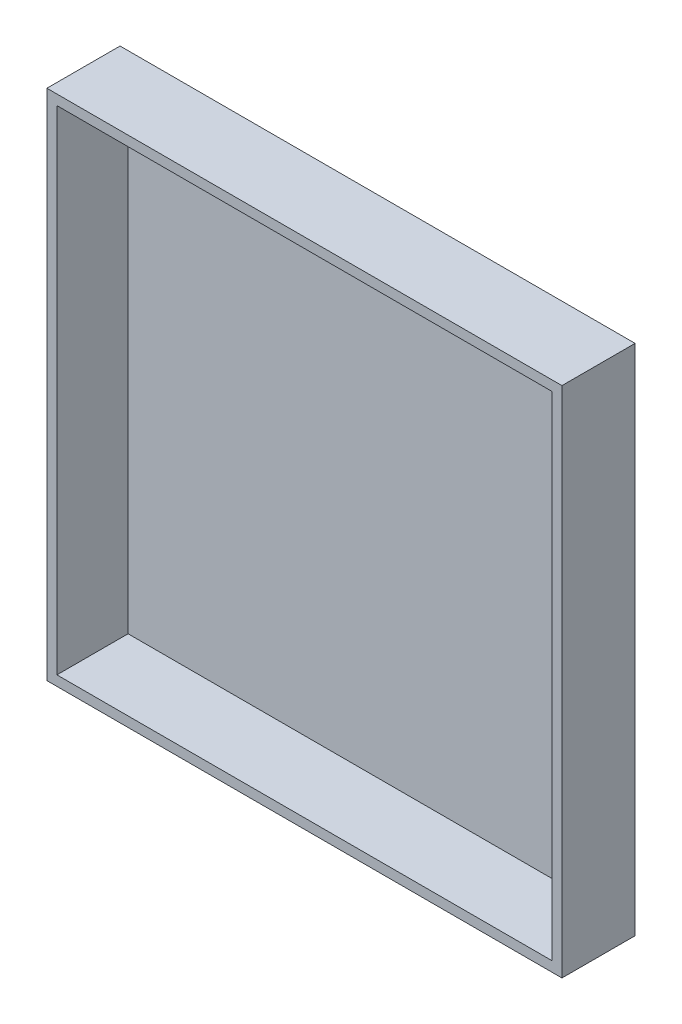
SolidWorks part; units mm, degrees
ref_plane "Front Plane" through (0, 0, 0) normal (0, 0, 1) x (1, 0, 0)
ref_plane "Top Plane" through (0, 0, 0) normal (0, 1, 0) x (1, 0, 0)
ref_plane "Right Plane" through (0, 0, 0) normal (1, 0, 0) x (0, 0, -1)
sketch "Sketch1" plane through (0, 0, 0) normal (0, 0, 1) x (1, 0, 0)
  line L1 (-247, 246) -> (247, 246)
  line L2 (-247, 246) -> (-247, -246)
  line L3 (-247, -246) -> (247, -246)
  line L4 (247, 246) -> (247, -246)
  line L5 (-247, 246) -> (247, -246) construction
  line L6 (-247, -246) -> (247, 246) construction
  point P0 (0, 0)
  dimension "D1" = 494
  dimension "D2" = 492
extrude "Extrude-Thin1" add sketch "Sketch1" along normal blind 71 thin thin type one direction wall 10
sketch "Sketch2" plane through (0, 0, 0) normal (0, 0, 1) x (1, 0, 0)
  line L4 (257, -256) -> (257, 256)
  line L5 (-257, -256) -> (257, -256)
  line L6 (-257, 256) -> (-257, -256)
  line L7 (257, 256) -> (-257, 256)
  line L8 (257, -256) -> (257, 256)
  line L9 (-257, -256) -> (257, -256)
  line L10 (-257, 256) -> (-257, -256)
  line L11 (257, 256) -> (-257, 256)
  dimension "D1" = 0
extrude "Boss-Extrude1" add sketch "Sketch2" against normal blind 2
